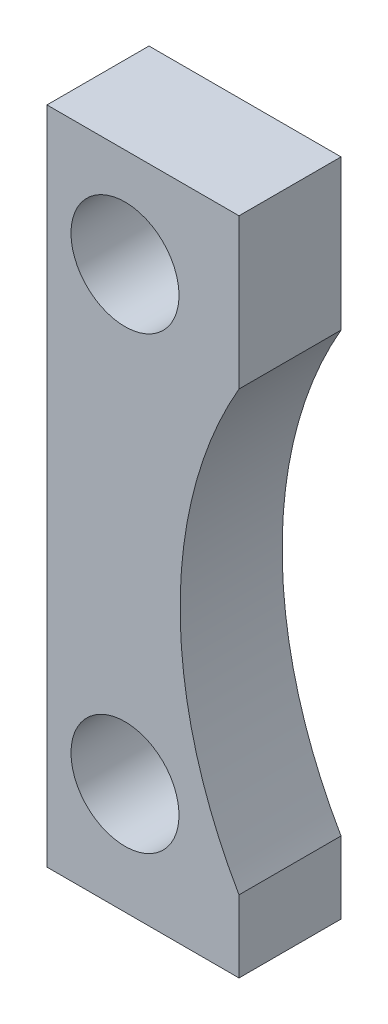
SolidWorks part; units mm, degrees
ref_plane "Ön Düzlem" through (0, 0, 0) normal (0, 0, 1) x (1, 0, 0)
ref_plane "Üst Düzlem" through (0, 0, 0) normal (0, 1, 0) x (1, 0, 0)
ref_plane "Sağ Düzlem" through (0, 0, 0) normal (1, 0, 0) x (0, 0, -1)
sketch "Çizim1" plane through (0, 0, 0) normal (0, 0, 1) x (1, 0, 0)
  line L0 (0, 110) -> (32, 110)
  line L1 (0, 110) -> (0, 0)
  line L2 (0, 0) -> (32, 0)
  line L3 (32, 110) -> (32, 85)
  line L4 (32, 12) -> (32, 0)
  arc A0 (32, 85) -> (32, 12) centre (95, 48.5) ccw
  dimension "D1" = 110
  dimension "D2" = 32
  dimension "D3" = 25
  dimension "D4" = 12
  dimension "D5" = 95
extrude "Yükseklik-Ekstrüzyon1" add sketch "Çizim1" along normal mid plane 17
sketch "Çizim2" plane through (0, 0, -8.5) normal (0, 0, -1) x (-1, 0, 0)
  line L1 (0, 110) -> (0, 0) construction
  line L2 (-32, 110) -> (0, 110) construction
  circle A0 centre (-13, 93.5) radius 9
  circle A1 centre (-13, 18.5) radius 9
  dimension "D2" = 18
  dimension "D1" = 75
  dimension "D3" = 13
  dimension "D4" = 16.5
extrude "Kes-Ekstrüzyon1" cut sketch "Çizim2" against normal through all
